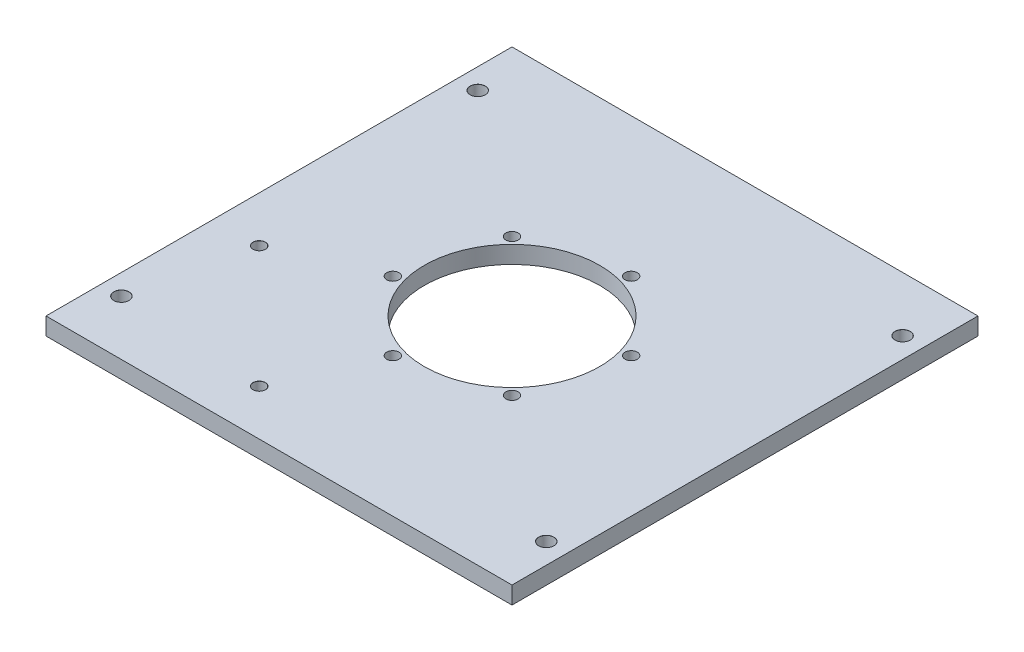
SolidWorks part; units mm, degrees
material "6061 Alloy"
ref_plane "Front Plane" through (0, 0, 0) normal (0, 0, 1) x (1, 0, 0)
ref_plane "Top Plane" through (0, 0, 0) normal (0, 1, 0) x (1, 0, 0)
ref_plane "Right Plane" through (0, 0, 0) normal (1, 0, 0) x (0, 0, -1)
sketch "Sketch1" plane through (0, 0, 0) normal (0, 1, 0) x (1, 0, 0)
  line L1 (-85, -85) -> (85, -85)
  line L2 (-85, -85) -> (-85, 85)
  line L3 (-85, 85) -> (85, 85)
  line L4 (85, -85) -> (85, 85)
  line L5 (-85, -85) -> (85, 85) construction
  line L6 (-85, 85) -> (85, -85) construction
  circle A1 centre (0, 0) radius 39.5
  arc A5 (-25.1023, 25.1023) -> (9.1881, 34.2904) centre (0, 0) cw
  arc A7 (9.1881, 34.2904) -> (-34.2904, -9.1881) centre (0, 0) ccw
  arc A9 (-34.2904, -9.1881) -> (-9.1881, -34.2904) centre (0, 0) ccw
  arc A11 (-9.1881, -34.2904) -> (25.1023, -25.1023) centre (0, 0) ccw
  circle A13 centre (0, 0) radius 32
  arc A14 (25.1023, -25.1023) -> (34.2904, 9.1881) centre (0, 0) ccw
extrude "Boss-Extrude3" add sketch "Sketch1" along normal blind 6.35
hole_wizard "M4 Clearance Hole2" positions "Sketch6" profile "Sketch7" hole size "M4" standard "ANSI Metric" end condition through all
sketch "Sketch6" plane through (0, 0, 0) normal (0, -1, 0) x (-1, 0, 0)
  point P0 (-9.1881, 34.2904)
  point P3 (25.1023, 25.1023)
  point P6 (34.2904, -9.1881)
  point P9 (9.1881, -34.2904)
  point P12 (-25.1023, -25.1023)
  point P15 (-34.2904, 9.1881)
sketch "Sketch7" plane through (9.1881, 0, -34.2904) normal (1, 0, 0) x (0, 0, -1)
  line L0 (0, 0) -> (0, 6.35)
  line L1 (0, 6.35) -> (2.25, 6.35)
  line L2 (2.25, 6.35) -> (2.25, 0.025)
  line L3 (2.25, 0.025) -> (2.275, 0)
  line L5 (2.275, 0) -> (0, 0)
  line L6 (-2.25, 0.025) -> (-2.275, 0) construction
  line L11 (0, -6.35) -> (0, 107.95) construction
  dimension "Thru Hole Dia." = 4.5
  dimension "Thru Hole Depth" = 6.35
  dimension "Near C'Sink Dia." = 4.55
  dimension "Near C'Sink Angle" = 90
sketch "Sketch13" plane through (0, 6.35, 0) normal (0, 1, 0) x (1, 0, 0)
  line L0 (-85, -85) -> (-46.1091, -46.1091)
  line L1 (-46.1091, -46.1091) -> (-68.3017, -23.9166)
  line L2 (-46.1091, -46.1091) -> (-23.9166, -68.3017)
hole_wizard "M4 Clearance Hole5" positions "Sketch14" profile "Sketch15" hole size "M4" standard "ANSI Metric" end condition through all
sketch "Sketch14" plane through (0, 6.35, 0) normal (0, 1, 0) x (1, 0, 0)
  point P0 (-68.3017, -23.9166)
  point P3 (-23.9166, -68.3017)
sketch "Sketch15" plane through (-68.3017, 6.35, 23.9166) normal (1, 0, 0) x (0, 0, 1)
  line L0 (0, 0) -> (0, 6.35)
  line L1 (0, 6.35) -> (2.25, 6.35)
  line L2 (2.25, 6.35) -> (2.25, 0.025)
  line L3 (2.25, 0.025) -> (2.275, 0)
  line L5 (2.275, 0) -> (0, 0)
  line L6 (-2.25, 0.025) -> (-2.275, 0) construction
  line L11 (0, -6.35) -> (0, 107.95) construction
  dimension "Thru Hole Dia." = 4.5
  dimension "Thru Hole Depth" = 6.35
  dimension "Near C'Sink Dia." = 4.55
  dimension "Near C'Sink Angle" = 90
sketch "Sketch16" plane through (0, 6.35, 0) normal (0, 1, 0) x (1, 0, 0)
  line L0 (-85, -85) -> (-55, -85)
  line L1 (-85, -85) -> (85, -85) construction
  line L2 (-55, -85) -> (-55, -70)
  line L3 (-85, -85) -> (-75, -85)
  line L4 (-75, -85) -> (-75, -70)
  line L5 (-75, -70) -> (-55, -70)
  line L6 (-85, 85) -> (-55, 85)
  line L7 (-85, 85) -> (85, 85) construction
  line L8 (85, 85) -> (55, 85)
  line L9 (85, -85) -> (55, -85)
  line L11 (-55, 85) -> (-75, 85)
  line L12 (-55, 85) -> (-55, 70)
  line L13 (-55, 70) -> (-75, 70)
  line L14 (-75, 85) -> (-75, 70)
  line L15 (55, 85) -> (75, 85)
  line L16 (55, 85) -> (55, 70)
  line L17 (55, 70) -> (75, 70)
  line L18 (75, 85) -> (75, 70)
  line L19 (55, -85) -> (75, -85)
  line L20 (55, -85) -> (55, -70)
  line L21 (55, -70) -> (75, -70)
  line L22 (75, -85) -> (75, -70)
sketch "Sketch23" plane through (0, 6.35, 0) normal (0, 1, 0) x (1, 0, 0)
  line L0 (-85, -85) -> (-85, -55)
  line L1 (-85, -85) -> (-85, 85) construction
  line L2 (-85, 85) -> (-85, 55)
  line L3 (85, 85) -> (85, 55)
  line L4 (-85, 85) -> (85, 85) construction
  line L5 (85, -85) -> (85, 85) construction
  line L6 (85, -85) -> (85, -55)
  line L8 (-85, 55) -> (-70, 55)
  line L9 (-85, 55) -> (-85, 75)
  line L10 (-85, 75) -> (-70, 75)
  line L11 (-70, 55) -> (-70, 75)
  line L12 (85, 55) -> (70, 55)
  line L13 (85, 55) -> (85, 75)
  line L14 (85, 75) -> (70, 75)
  line L15 (70, 55) -> (70, 75)
  line L16 (85, -55) -> (70, -55)
  line L17 (85, -55) -> (85, -75)
  line L18 (85, -75) -> (70, -75)
  line L19 (70, -55) -> (70, -75)
  line L20 (-85, -55) -> (-70, -55)
  line L21 (-85, -55) -> (-85, -75)
  line L22 (-85, -75) -> (-70, -75)
  line L23 (-70, -55) -> (-70, -75)
hole_wizard "M5 Clearance Hole1" positions "Sketch24" profile "Sketch25" hole size "M5" standard "ANSI Metric" end condition through all
sketch "Sketch24" plane through (0, 6.35, 0) normal (0, 1, 0) x (1, 0, 0)
  point P0 (-77.5, 65)
  point P2 (77.5, 65)
  point P4 (77.5, -65)
  point P6 (-77.5, -65)
sketch "Sketch25" plane through (-77.5, 6.35, -65) normal (1, 0, 0) x (0, 0, 1)
  line L0 (0, 0) -> (0, 6.35)
  line L1 (0, 6.35) -> (2.75, 6.35)
  line L2 (2.75, 6.35) -> (2.75, 0.025)
  line L3 (2.75, 0.025) -> (2.775, 0)
  line L5 (2.775, 0) -> (0, 0)
  line L6 (-2.75, 0.025) -> (-2.775, 0) construction
  line L11 (0, -6.35) -> (0, 107.95) construction
  dimension "Thru Hole Dia." = 5.5
  dimension "Thru Hole Depth" = 6.35
  dimension "Near C'Sink Dia." = 5.55
  dimension "Near C'Sink Angle" = 90
